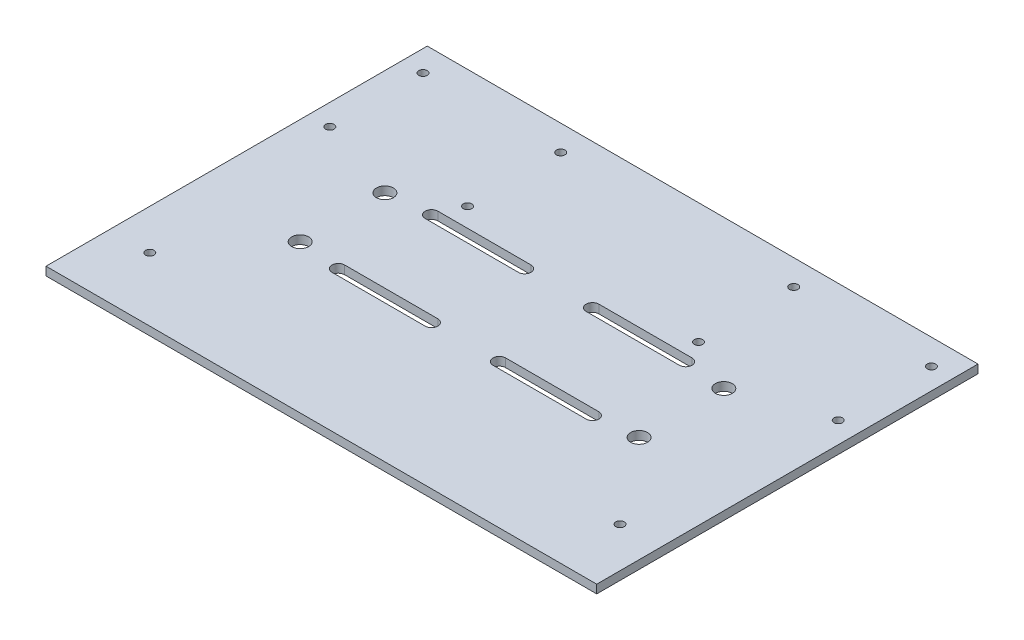
SolidWorks part; units mm, degrees
ref_plane "Front Plane" through (0, 0, 0) normal (0, 0, 1) x (1, 0, 0)
ref_plane "Top Plane" through (0, 0, 0) normal (0, 1, 0) x (1, 0, 0)
ref_plane "Right Plane" through (0, 0, 0) normal (1, 0, 0) x (0, 0, -1)
sketch "Sketch1" plane through (0, 0, 0) normal (0, 1, 0) x (1, 0, 0)
  line L1 (-8.2126, -4.5965) -> (121.7874, -4.5965)
  line L2 (-8.2126, -4.5965) -> (-8.2126, 85.4035)
  line L3 (-8.2126, 85.4035) -> (121.7874, 85.4035)
  line L4 (121.7874, -4.5965) -> (121.7874, 85.4035)
  dimension "D1" = 130
  dimension "D2" = 90
extrude "Boss-Extrude2" add sketch "Sketch1" along normal blind 2
sketch "Sketch2" plane through (0, 2, 0) normal (0, 1, 0) x (1, 0, 0)
  line L0 (121.7874, 85.4035) -> (-8.2126, 85.4035) construction
  line L1 (16.7874, 50.4035) -> (96.7874, 50.4035)
  line L2 (16.7874, 50.4035) -> (16.7874, 30.4035)
  line L3 (16.7874, 30.4035) -> (96.7874, 30.4035)
  line L4 (96.7874, 50.4035) -> (96.7874, 30.4035)
  line L5 (-8.2126, 85.4035) -> (-8.2126, -4.5965) construction
  circle A0 centre (16.7874, 50.4035) radius 2
  circle A1 centre (16.7874, 30.4035) radius 2
  circle A2 centre (96.7874, 50.4035) radius 2
  circle A3 centre (96.7874, 30.4035) radius 2
  point P6 (16.7874, 40.4035)
  point P7 (56.7874, 50.4035)
  dimension "D1" = 20
  dimension "D2" = 80
  dimension "D3" = 45
  dimension "D4" = 65
extrude "Cut-Extrude1" cut sketch "Sketch2" against normal blind 10 contours A0 | A1 | A3 | A2
sketch "Sketch4" plane through (0, 2, 0) normal (0, 1, 0) x (1, 0, 0)
  line L0 (26.7874, 51.4035) -> (48.7874, 51.4035) construction
  line L1 (26.7874, 52.9035) -> (48.7874, 52.9035)
  line L2 (26.7874, 49.9035) -> (48.7874, 49.9035)
  line L3 (26.7874, 29.4035) -> (48.7874, 29.4035) construction
  line L4 (26.7874, 30.9035) -> (48.7874, 30.9035)
  line L5 (26.7874, 27.9035) -> (48.7874, 27.9035)
  line L6 (64.7874, 51.4035) -> (86.7874, 51.4035) construction
  line L7 (64.7874, 52.9035) -> (86.7874, 52.9035)
  line L8 (64.7874, 49.9035) -> (86.7874, 49.9035)
  line L9 (64.7874, 29.4035) -> (86.7874, 29.4035) construction
  line L10 (64.7874, 30.9035) -> (86.7874, 30.9035)
  line L11 (64.7874, 27.9035) -> (86.7874, 27.9035)
  arc A0 (26.7874, 52.9035) -> (26.7874, 49.9035) centre (26.7874, 51.4035) ccw
  arc A1 (48.7874, 49.9035) -> (48.7874, 52.9035) centre (48.7874, 51.4035) ccw
  arc A2 (26.7874, 30.9035) -> (26.7874, 27.9035) centre (26.7874, 29.4035) ccw
  arc A3 (48.7874, 27.9035) -> (48.7874, 30.9035) centre (48.7874, 29.4035) ccw
  arc A4 (64.7874, 52.9035) -> (64.7874, 49.9035) centre (64.7874, 51.4035) ccw
  arc A5 (86.7874, 49.9035) -> (86.7874, 52.9035) centre (86.7874, 51.4035) ccw
  arc A6 (64.7874, 30.9035) -> (64.7874, 27.9035) centre (64.7874, 29.4035) ccw
  arc A7 (86.7874, 27.9035) -> (86.7874, 30.9035) centre (86.7874, 29.4035) ccw
  circle A8 centre (16.7874, 30.4035) radius 2 construction
  circle A10 centre (16.7874, 50.4035) radius 2 construction
  circle A12 centre (96.7874, 30.4035) radius 2 construction
  circle A14 centre (96.7874, 50.4035) radius 2 construction
  point P2 (37.7874, 51.4035)
  point P7 (37.7874, 29.4035)
  point P14 (75.7874, 51.4035)
  point P21 (75.7874, 29.4035)
  dimension "D1" = 1.5
  dimension "D2" = 1.5
  dimension "D3" = 1.5
  dimension "D5" = 1.5
  dimension "D4" = 10
  dimension "D13" = 10
  dimension "D14" = 10
  dimension "D6" = 22
  dimension "D7" = 22
  dimension "D8" = 22
  dimension "D9" = 22
  dimension "D10" = 22
  dimension "D11" = 21
  dimension "D12" = 0
extrude "Cut-Extrude3" cut sketch "Sketch4" against normal blind 10
sketch "Sketch5" plane through (0, 2, 0) normal (0, 1, 0) x (1, 0, 0)
  line L0 (-8.2126, 40.4035) -> (121.7874, 40.4035) construction
  line L1 (-8.2126, 85.4035) -> (-8.2126, -4.5965) construction
  line L2 (121.7874, -4.5965) -> (121.7874, 85.4035) construction
  line L3 (56.7874, 85.4035) -> (56.7874, -4.5965) construction
  line L4 (121.7874, 85.4035) -> (-8.2126, 85.4035) construction
  line L5 (-8.2126, -4.5965) -> (121.7874, -4.5965) construction
  line L6 (-3.2126, 57.4035) -> (29.2874, 57.4035)
  line L7 (84.2874, 57.4035) -> (116.7874, 57.4035)
  line L8 (84.2874, 57.4035) -> (84.2874, 79.4035)
  line L9 (84.2874, 79.4035) -> (116.7874, 79.4035)
  line L10 (116.7874, 57.4035) -> (116.7874, 79.4035)
  line L11 (-3.2126, 57.4035) -> (-3.2126, 79.4035)
  line L12 (-3.2126, 79.4035) -> (29.2874, 79.4035)
  line L13 (29.2874, 57.4035) -> (29.2874, 79.4035)
  circle A0 centre (1.2874, 10.4035) radius 1
  circle A1 centre (112.2874, 10.4035) radius 1
  circle A2 centre (84.2874, 56.9208) radius 1
  circle A3 centre (116.7874, 57.4035) radius 1
  circle A4 centre (116.7874, 79.4035) radius 1
  circle A5 centre (84.2874, 79.4035) radius 1
  circle A6 centre (-3.2126, 57.4035) radius 1
  circle A7 centre (29.2874, 57.4035) radius 1
  circle A8 centre (29.2874, 79.4035) radius 1
  circle A9 centre (-3.2126, 79.4035) radius 1
  point P29 (0, 0)
  point P34 (0, 0)
  point P35 (0, 0)
  dimension "D3" = 2
  dimension "D4" = 2
  dimension "D5" = 111
  dimension "D6" = 55.5
  dimension "D11" = 27.5
  dimension "D1" = 30
  dimension "D2" = 0
  dimension "D7" = 22
  dimension "D8" = 32.5
  dimension "D9" = 39
  dimension "D10" = 27.5
  dimension "D12" = 39
extrude "Cut-Extrude4" cut sketch "Sketch5" against normal blind 10 contours A0 | A1 | A2 | A3 | A4 | A5 | A8 | A7 | A6 | A9
